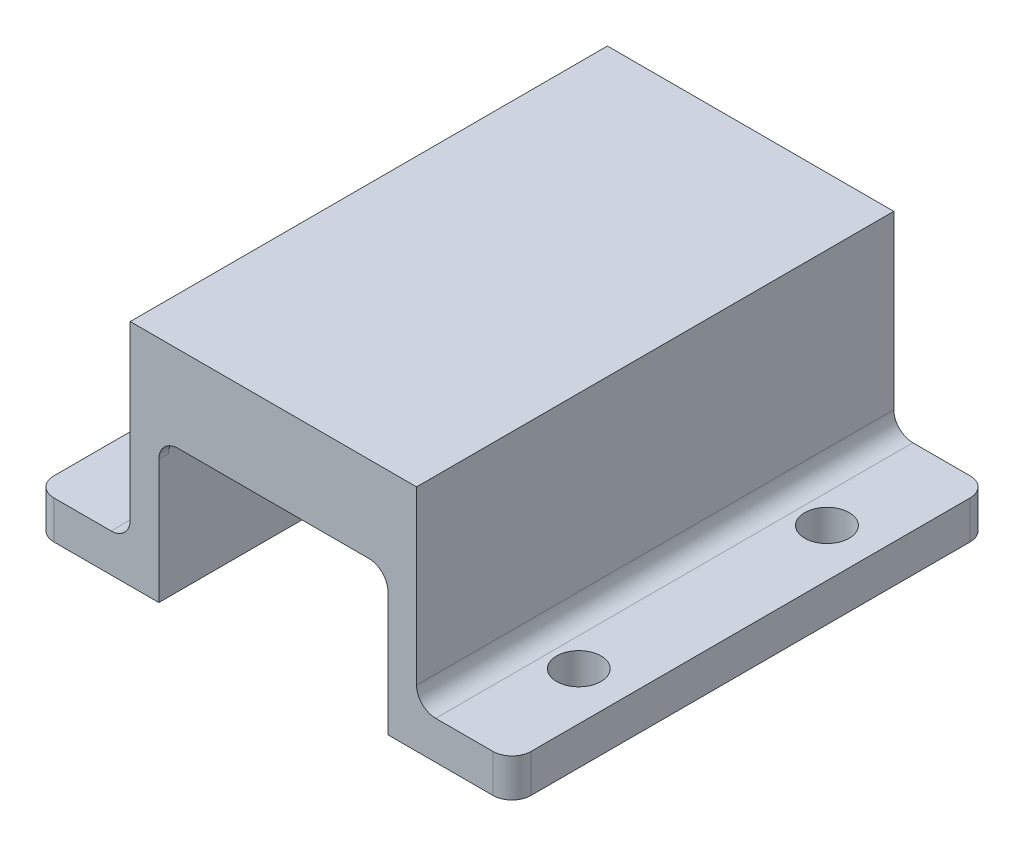
SolidWorks part; units mm, degrees
ref_plane "Front Plane" through (0, 0, 0) normal (0, 0, 1) x (1, 0, 0)
ref_plane "Top Plane" through (0, 0, 0) normal (0, 1, 0) x (1, 0, 0)
ref_plane "Right Plane" through (0, 0, 0) normal (1, 0, 0) x (0, 0, -1)
sketch "Sketch1" plane through (0, 0, 0) normal (0, 0, 1) x (1, 0, 0)
  line L1 (0, 0) -> (15, 0)
  line L2 (0, 0) -> (0, 12)
  line L3 (0, 12) -> (15, 12)
  line L4 (15, 0) -> (15, 12)
  dimension "D1" = 12
  dimension "D2" = 15
extrude "Boss-Extrude1" add sketch "Sketch1" along normal blind 30
sketch "Sketch3" plane through (0, 0, 30) normal (0, 0, 1) x (1, 0, 0)
  line L0 (0, 0) -> (15, 0) construction
  line L1 (1.5, 0) -> (13.5, 0)
  line L2 (1.5, 0) -> (1.5, 10)
  line L3 (1.5, 10) -> (13.5, 10)
  line L4 (13.5, 0) -> (13.5, 10)
  line L5 (15, 12) -> (0, 12) construction
  point P6 (7.5, 0)
  point P9 (7.5, 12)
  dimension "D1" = 12
  dimension "D2" = 10
extrude "Cut-Extrude1" cut sketch "Sketch3" against normal blind 30 contours L3 L4 L1 L2
fillet "Fillet1" radius 1 2 edges at (13.5, 10, 15) (1.5, 10, 15)
sketch "Sketch4" plane through (0, 10, 0) normal (0, -1, 0) x (1, 0, 0)
  line L0 (1.5, 0) -> (1.5, 30) construction
  line L1 (13.5, 30) -> (1.5, 30)
  line L2 (13.5, 30) -> (13.5, 29.5)
  line L3 (13.5, 29.5) -> (1.5, 29.5)
  line L4 (1.5, 30) -> (1.5, 29.5)
  line L5 (13.5, 30) -> (13.5, 0) construction
  line L6 (13.5, 5.5) -> (1.5, 5.5)
  line L7 (13.5, 5.5) -> (13.5, 5)
  line L8 (13.5, 5) -> (1.5, 5)
  line L9 (1.5, 5.5) -> (1.5, 5)
  line L10 (1.5, 0) -> (1.5, 30) construction
  dimension "D1" = 0.5
  dimension "D2" = 0.5
  dimension "D3" = 24
extrude "Boss-Extrude3" add sketch "Sketch4" along normal blind 2.5
sketch "Sketch5" plane through (0, 0, 0) normal (0, -1, 0) x (1, 0, 0)
  line L0 (0, 30) -> (0, 0) construction
  line L1 (15, 0) -> (0, 0)
  line L2 (15, 0) -> (15, 5)
  line L3 (15, 5) -> (0, 5)
  line L4 (0, 0) -> (0, 5)
  line L5 (12.5, 5) -> (13.5, 5) construction
  dimension "D1" = 0
extrude "Cut-Extrude2" cut sketch "Sketch5" against normal through all both and the other way through all
sketch "Sketch6" plane through (0, 0, 0) normal (0, -1, 0) x (1, 0, 0)
  line L0 (13.5, 30) -> (15, 30) construction
  line L1 (15, 5) -> (20, 5)
  line L2 (15, 5) -> (15, 30)
  line L3 (15, 30) -> (20, 30)
  line L4 (20, 5) -> (20, 30)
  line L5 (7.5, 30) -> (7.5, 5) construction
  line L6 (13.5, 30) -> (1.5, 30) construction
  line L7 (1.5, 5) -> (13.5, 5) construction
  line L8 (0, 30) -> (-5, 30)
  line L9 (-5, 5) -> (-5, 30)
  line L10 (0, 5) -> (-5, 5)
  line L11 (0, 5) -> (0, 30)
  circle A0 centre (17.5, 24) radius 1.163
  circle A1 centre (17.5, 11) radius 1.1649
  circle A2 centre (-2.5, 11) radius 1.1649
  circle A3 centre (-2.5, 24) radius 1.163
  point P12 (17.5, 5)
  dimension "D1" = 5
  dimension "D2" = 6
  dimension "D3" = 6
extrude "Boss-Extrude4" add sketch "Sketch6" against normal blind 2
fillet "Fillet2" radius 1 10 edges at (1.5, 7.5, 29.75) (13.5, 7.5, 29.75) (13.5, 7.5, 5.25) (1.5, 7.5, 5.25) (-5, 1, 30) (-5, 1, 5) (0, 2, 17.5) (20, 1, 5) (20, 1, 30) (15, 2, 17.5)
